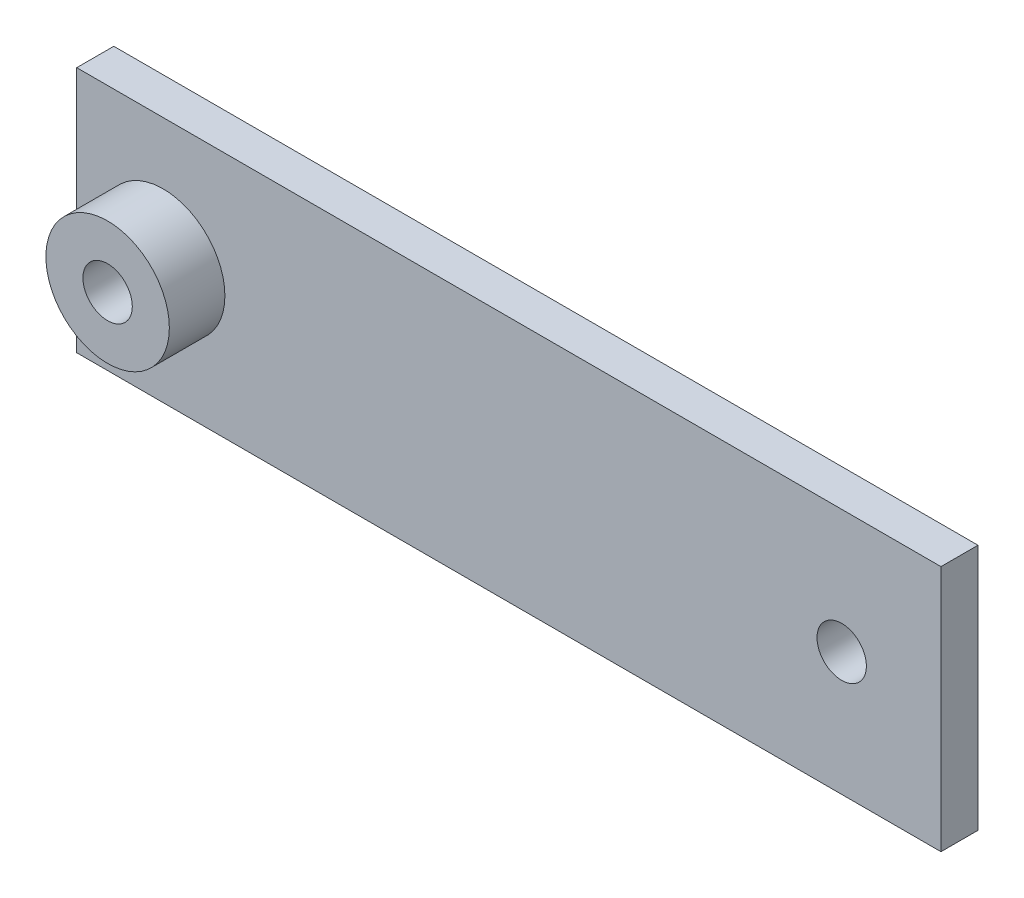
SolidWorks part; units mm, degrees
ref_plane "Front Plane" through (0, 0, 0) normal (0, 0, 1) x (1, 0, 0)
ref_plane "Top Plane" through (0, 0, 0) normal (0, 1, 0) x (1, 0, 0)
ref_plane "Right Plane" through (0, 0, 0) normal (1, 0, 0) x (0, 0, -1)
sketch "Sketch1" plane through (0, 0, 0) normal (0, 0, 1) x (1, 0, 0)
  line L1 (-35, 10) -> (35, 10)
  line L2 (-35, 10) -> (-35, -10)
  line L3 (-35, -10) -> (35, -10)
  line L4 (35, 10) -> (35, -10)
  line L5 (-35, 10) -> (35, -10) construction
  line L6 (-35, -10) -> (35, 10) construction
  point P0 (0, 0)
  dimension "D1" = 70
  dimension "D2" = 20
extrude "Boss-Extrude1" add sketch "Sketch1" along normal blind 3
sketch "Sketch2" plane through (0, 0, 3) normal (0, 0, 1) x (1, 0, 0)
  line L1 (-35, 10) -> (-35, -10) construction
  circle A0 centre (-28, 0) radius 2
  circle A1 centre (26.96, 0) radius 2
  dimension "D1" = 4
  dimension "D2" = 4
  dimension "D3" = 54.96
  dimension "D4" = 7
extrude "Cut-Extrude2" cut sketch "Sketch2" against normal through all
sketch "Sketch3" plane through (0, 0, 3) normal (0, 0, 1) x (1, 0, 0)
  circle A0 centre (-28, 0) radius 5
  dimension "D1" = 10
extrude "Boss-Extrude2" add sketch "Sketch3" along normal blind 4.5
sketch "Sketch4" plane through (0, 0, 7.5) normal (0, 0, 1) x (1, 0, 0)
  circle A0 centre (-28, 0) radius 2
  dimension "D1" = 4
extrude "Cut-Extrude3" cut sketch "Sketch4" against normal blind 4.5
